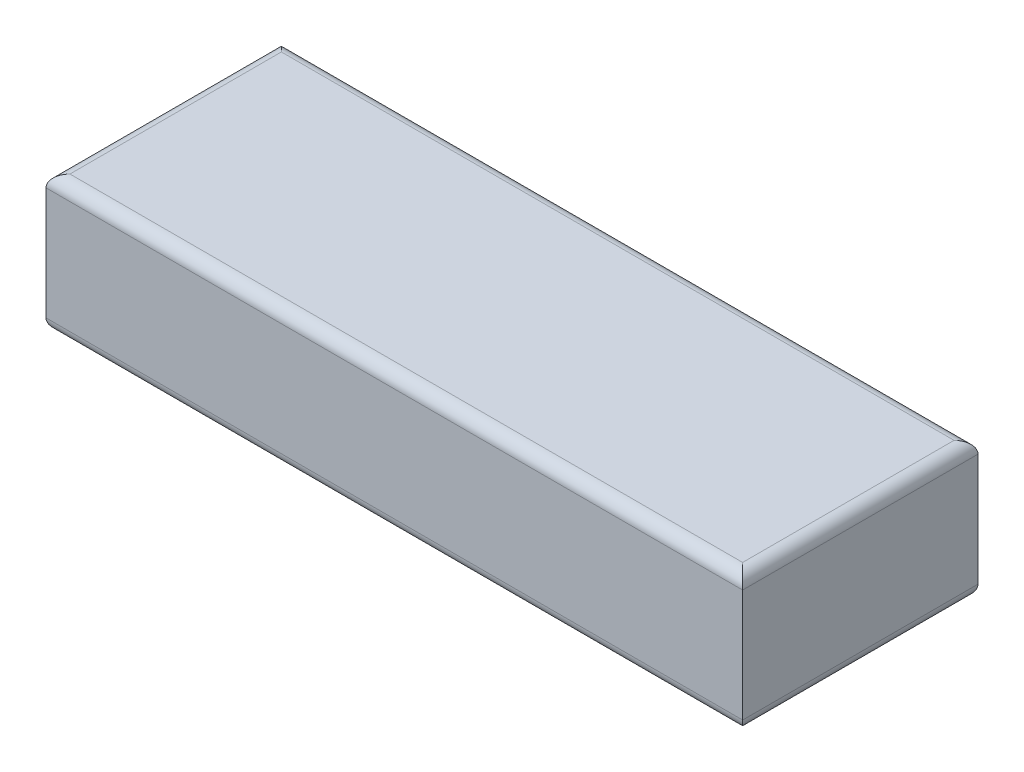
SolidWorks part; units mm, degrees
ref_plane "Front Plane" through (0, 0, 0) normal (0, 0, 1) x (1, 0, 0)
ref_plane "Top Plane" through (0, 0, 0) normal (0, 1, 0) x (1, 0, 0)
ref_plane "Right Plane" through (0, 0, 0) normal (1, 0, 0) x (0, 0, -1)
sketch "Sketch1" plane through (0, 0, 0) normal (0, 1, 0) x (1, 0, 0)
  line L1 (-2.7063, -52.4148) -> (145.2937, -52.4148)
  line L2 (-2.7063, -52.4148) -> (-2.7063, -2.4148)
  line L3 (-2.7063, -2.4148) -> (145.2937, -2.4148)
  line L4 (145.2937, -52.4148) -> (145.2937, -2.4148)
  dimension "D1" = 50
  dimension "D2" = 148
extrude "Boss-Extrude1" add sketch "Sketch1" along normal blind 29
fillet "Fillet1" radius 2.54 8 edges at (71.2937, 0, 2.4148) (145.2937, 0, 27.4148) (71.2937, 0, 52.4148) (-2.7063, 0, 27.4148) (71.2937, 29, 52.4148) (145.2937, 29, 27.4148) (71.2937, 29, 2.4148) (-2.7063, 29, 27.4148)
